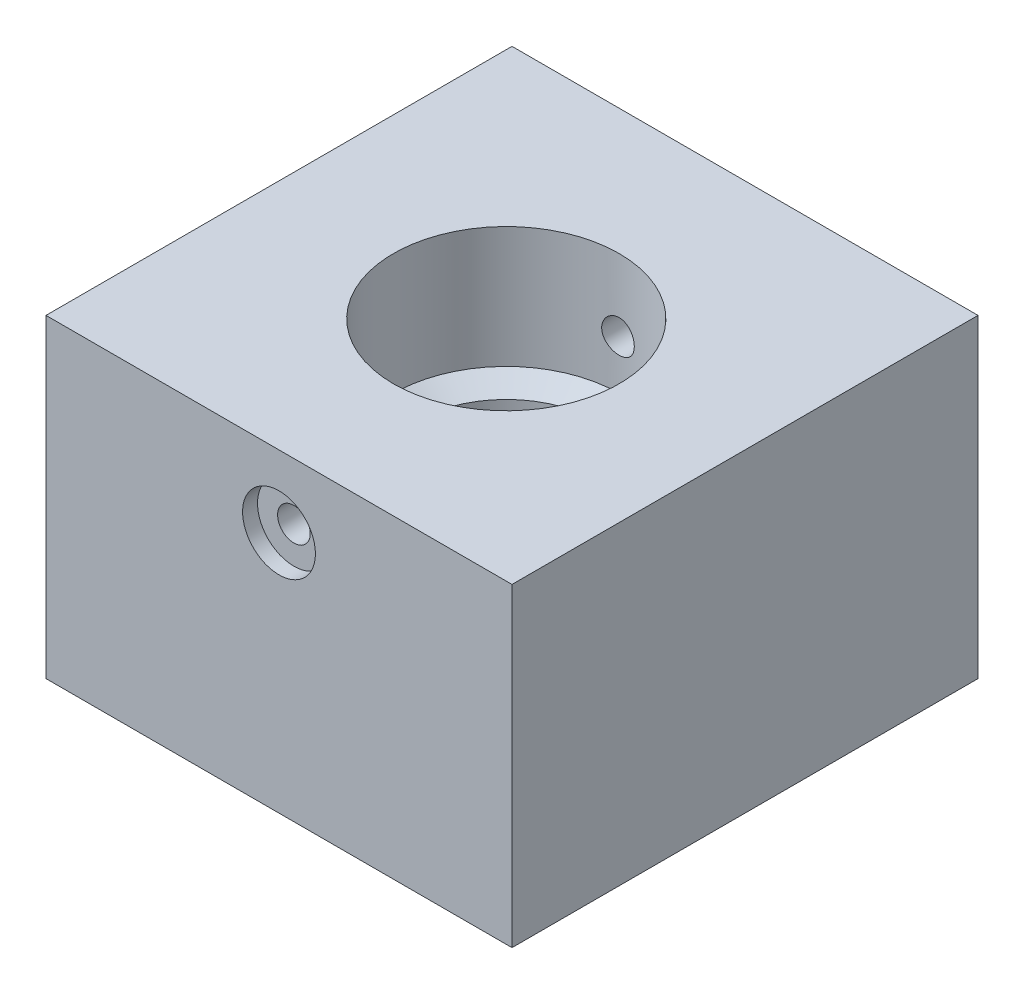
SolidWorks part; units mm, degrees
ref_plane "Front Plane" through (0, 0, 0) normal (0, 0, 1) x (1, 0, 0)
ref_plane "Top Plane" through (0, 0, 0) normal (0, 1, 0) x (1, 0, 0)
ref_plane "Right Plane" through (0, 0, 0) normal (1, 0, 0) x (0, 0, -1)
sketch "Sketch1" plane through (0, 0, 0) normal (0, 1, 0) x (1, 0, 0)
  line L0 (-12.6151, 13.011) -> (-12.6151, -12.389)
  line L1 (-12.6151, -12.389) -> (12.7849, -12.389)
  line L2 (12.7849, -12.389) -> (12.7849, 13.011)
  line L3 (12.7849, 13.011) -> (-12.6151, 13.011)
  point P5 (0, 0)
  dimension "D1" = 25.4
  dimension "D2" = 25.4
sketch "Sketch2" plane through (0, 0, 0) normal (1, 0, 0) x (0, 0, -1)
  line L0 (-12.389, 0) -> (-12.389, -17.1469)
  line L1 (-12.389, 0) -> (13.011, 0) construction
  line L2 (13.011, 0) -> (-12.389, 0) construction
  line L3 (-12.389, -17.1469) -> (13.011, -17.1469)
  line L4 (13.011, -17.1469) -> (13.011, 0)
  line L5 (-12.389, 0) -> (13.011, 0)
extrude "Boss-Extrude1" add sketch "Sketch2" along normal mid plane 25.4
sketch "Sketch4" plane through (0, 0, 0) normal (0, 1, 0) x (1, 0, 0)
  point P0 (0, 0)
hole_wizard "7/16-20 Tapped Hole1" positions "Sketch4" profile "Sketch5" tap size "7/16-20" standard "ANSI Inch"
sketch "Sketch5" plane through (0, 0, 0) normal (1, 0, 0) x (0, 0, 1)
  line L0 (0, 0) -> (0, 15.2165)
  line L1 (0, 15.2165) -> (4.9606, 12.2359)
  line L2 (4.9606, 12.2359) -> (4.9606, 0)
  line L5 (4.9606, 0) -> (0, 0)
  line L10 (0, 15.2165) -> (-4.9606, 12.2359) construction
  line L11 (0, -6.35) -> (0, 107.95) construction
  dimension "Tap Drill Dia." = 9.9212
  dimension "Tap Drill Depth" = 15.2165
  dimension "Drill Angle" = 118
hole_wizard "7/16 Clearance Hole3" positions "Sketch1" profile "Sketch8" hole size "7/16" standard "ANSI Inch"
sketch "Sketch8" plane through (0, 0, 0) normal (1, 0, 0) x (0, 0, 1)
  line L0 (0, 0) -> (0, 10.3004)
  line L1 (0, 10.3004) -> (6.1519, 6.604)
  line L2 (6.1519, 6.604) -> (6.1519, 0)
  line L5 (6.1519, 0) -> (0, 0)
  line L10 (0, 10.3004) -> (-6.1519, 6.604) construction
  line L11 (0, -6.35) -> (0, 107.95) construction
  dimension "Hole Dia." = 12.3038
  dimension "Hole Depth" = 6.604
  dimension "Drill Angle" = 118
sketch "Sketch12" plane through (0, 0, 12.389) normal (0, 0, 1) x (1, 0, 0)
  line L0 (0, 0) -> (0, -17.1469) construction
  line L1 (12.7, -17.1469) -> (-12.7, -17.1469) construction
hole_wizard "CBORE for #0 Binding Head Machine Screw1" positions "3DSketch7" profile "Sketch13" counterbore size "#0" standard "ANSI Inch" end condition through all
sketch3d "3DSketch7"
  line L0 (0, 0, 12.389) -> (0, -17.1469, 12.389) construction
  point P0 (0, -3.9143, 12.389)
sketch "Sketch13" plane through (0, -3.9143, 12.389) normal (1, 0, 0) x (0, -1, 0)
  line L0 (0, 0) -> (0, 25.4)
  line L1 (0, 25.4) -> (0.889, 25.4)
  line L3 (0.889, 25.4) -> (0.889, 0.8128)
  line L4 (0.889, 0.8128) -> (1.985, 0.8128)
  line L5 (1.985, 0.8128) -> (1.985, 0)
  line L7 (1.985, 0) -> (0, 0)
  line L11 (0, -6.35) -> (0, 107.95) construction
  dimension "Thru Hole Dia." = 1.778
  dimension "Thru Hole Depth" = 25.4
  dimension "C'Bore Dia." = 3.97
  dimension "C'Bore Depth" = 0.8128
